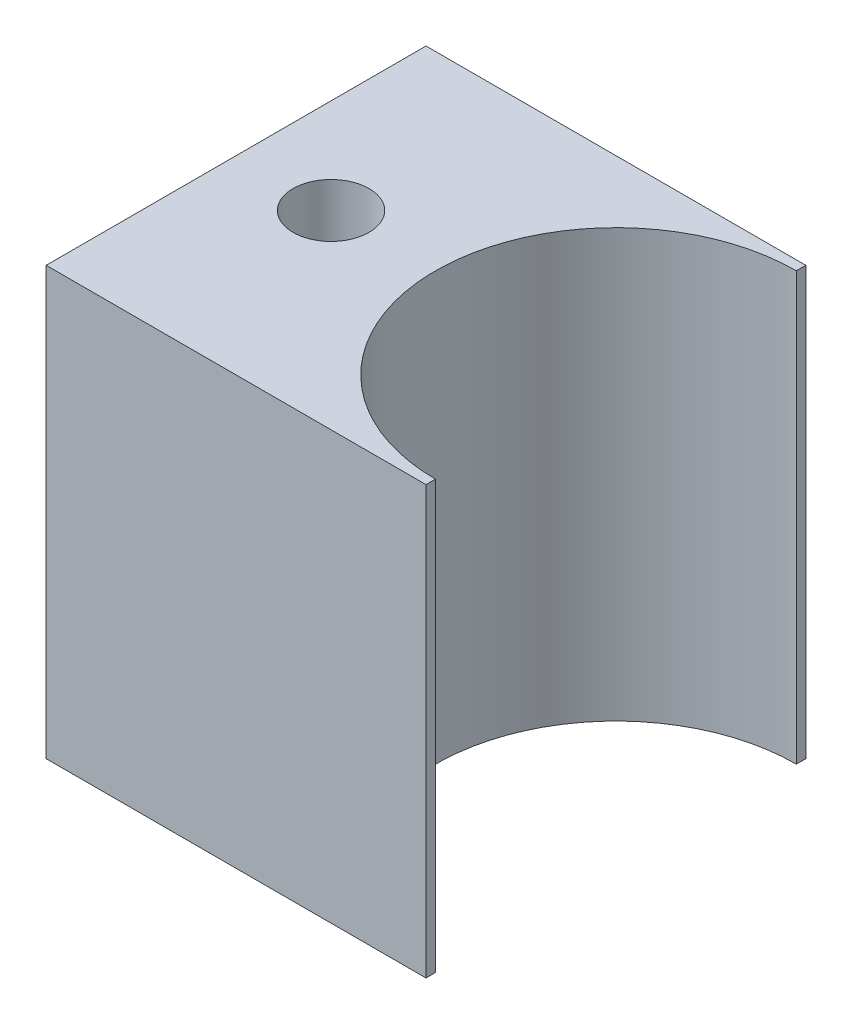
SolidWorks part; units mm, degrees
ref_plane "Front Plane" through (0, 0, 0) normal (0, 0, 1) x (1, 0, 0)
ref_plane "Top Plane" through (0, 0, 0) normal (0, 1, 0) x (1, 0, 0)
ref_plane "Right Plane" through (0, 0, 0) normal (1, 0, 0) x (0, 0, -1)
sketch "Sketch3" plane through (0, 0, 0) normal (0, 1, 0) x (1, 0, 0)
  line L0 (0, 0) -> (0, 0.635)
  line L1 (0, 0) -> (-25.4, 0)
  line L2 (-25.4, 0) -> (-25.4, 25.4)
  line L3 (-25.4, 25.4) -> (0, 25.4)
  line L4 (0, 25.4) -> (0, 24.765)
  arc A0 (0, 0.635) -> (0, 24.765) centre (0, 12.7) cw
extrude "Boss-Extrude1" add sketch "Sketch3" along normal blind 28.575 contours L3 L4 A0 L0 L1 L2
sketch "Sketch6" plane through (0, 0, 0) normal (0, -1, 0) x (-1, 0, 0)
  circle A0 centre (19.05, 12.7) radius 2.54
extrude "Cut-Extrude4" cut sketch "Sketch6" against normal blind 28.575
